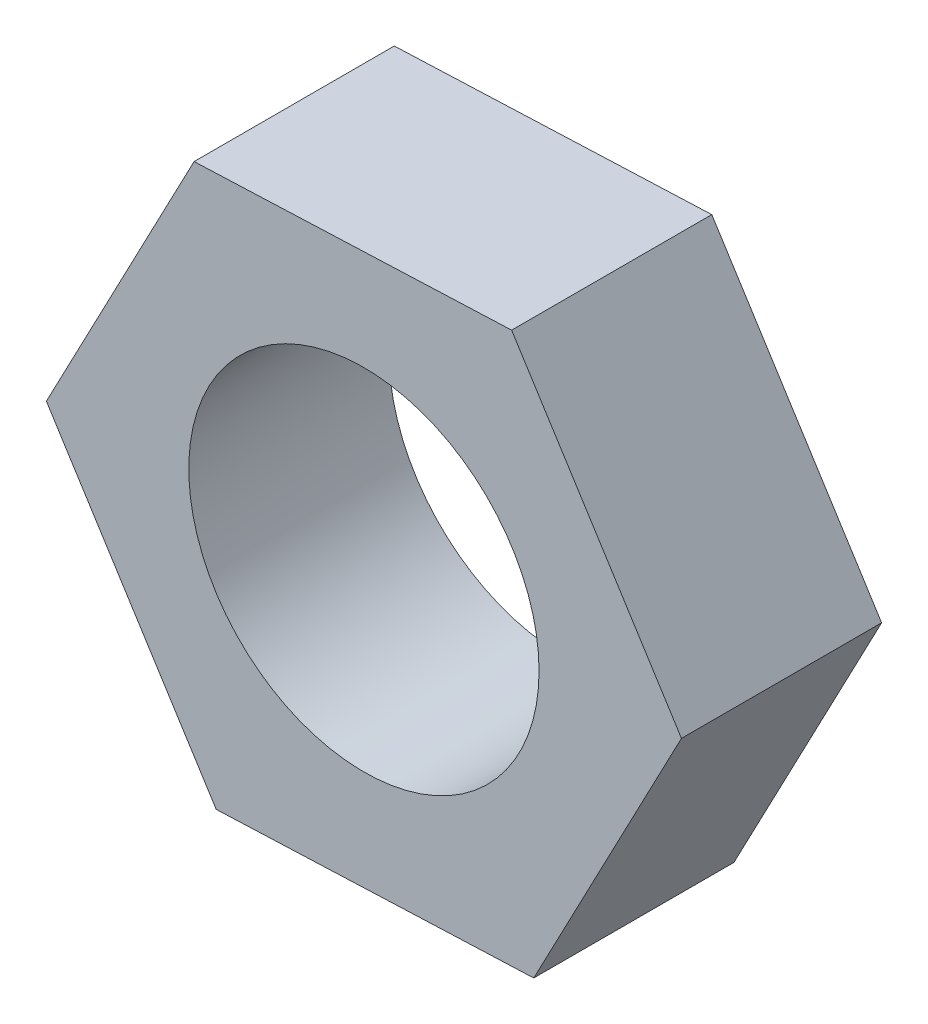
SolidWorks part; units mm, degrees
material "Plain Carbon Steel"
ref_plane "Front" through (0, 0, 0) normal (0, 0, 1) x (1, 0, 0)
ref_plane "Top" through (0, 0, 0) normal (0, 1, 0) x (1, 0, 0)
ref_plane "Right" through (0, 0, 0) normal (1, 0, 0) x (0, 0, -1)
sketch "Sketch1" plane through (0, 0, 0) normal (0, 0, 1) x (1, 0, 0)
  line L1 (3.394, -5.3679) -> (6.3457, 0.2553)
  line L2 (6.3457, 0.2553) -> (2.9518, 5.6232)
  line L3 (2.9518, 5.6232) -> (-3.394, 5.3679)
  line L4 (-3.394, 5.3679) -> (-6.3457, -0.2553)
  line L5 (-6.3457, -0.2553) -> (-2.9518, -5.6232)
  line L6 (-2.9518, -5.6232) -> (3.394, -5.3679)
  circle A0 centre (0, 0) radius 5.5 construction
  circle A1 centre (0, 0) radius 3.5
  dimension "D1" = 11
  dimension "D2" = 7
extrude "Boss-Extrude1" add sketch "Sketch1" along normal blind 4
